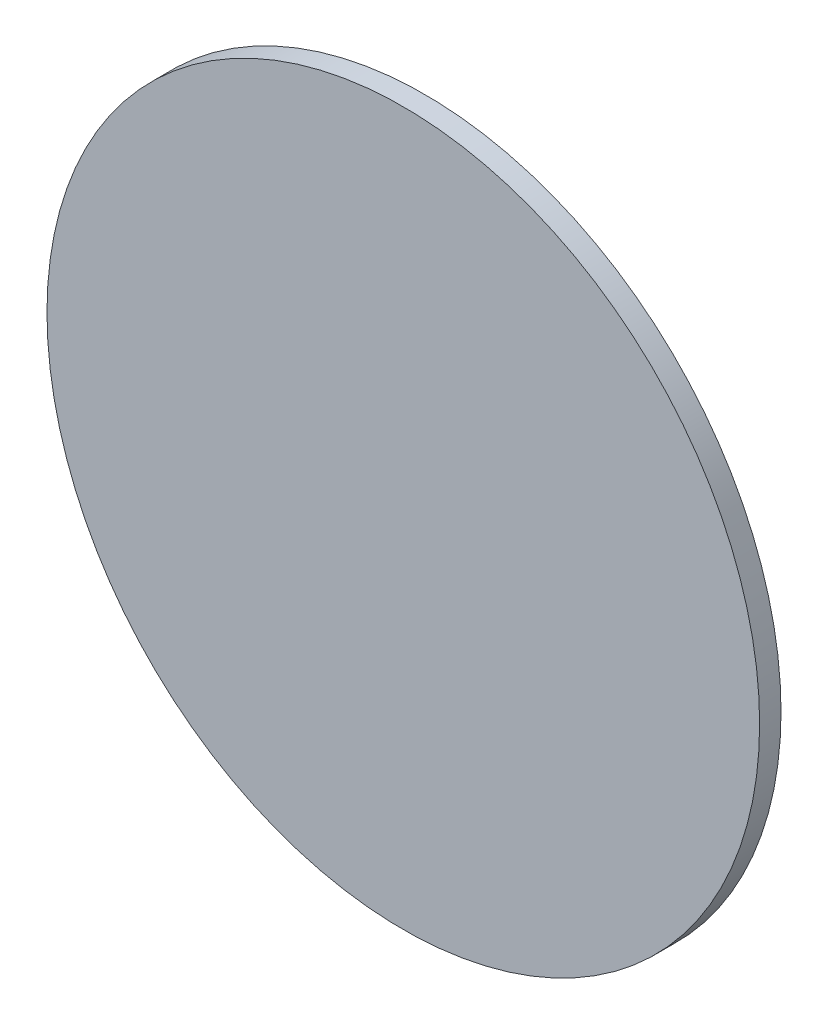
SolidWorks part; units mm, degrees
ref_plane "Front Plane" through (0, 0, 0) normal (0, 0, 1) x (1, 0, 0)
ref_plane "Top Plane" through (0, 0, 0) normal (0, 1, 0) x (1, 0, 0)
ref_plane "Right Plane" through (0, 0, 0) normal (1, 0, 0) x (0, 0, -1)
sketch "Sketch1" plane through (0, 0, 0) normal (0, 0, 1) x (1, 0, 0)
  circle A0 centre (0, 0) radius 50
extrude "Boss-Extrude1" add sketch "Sketch1" along normal blind 3
